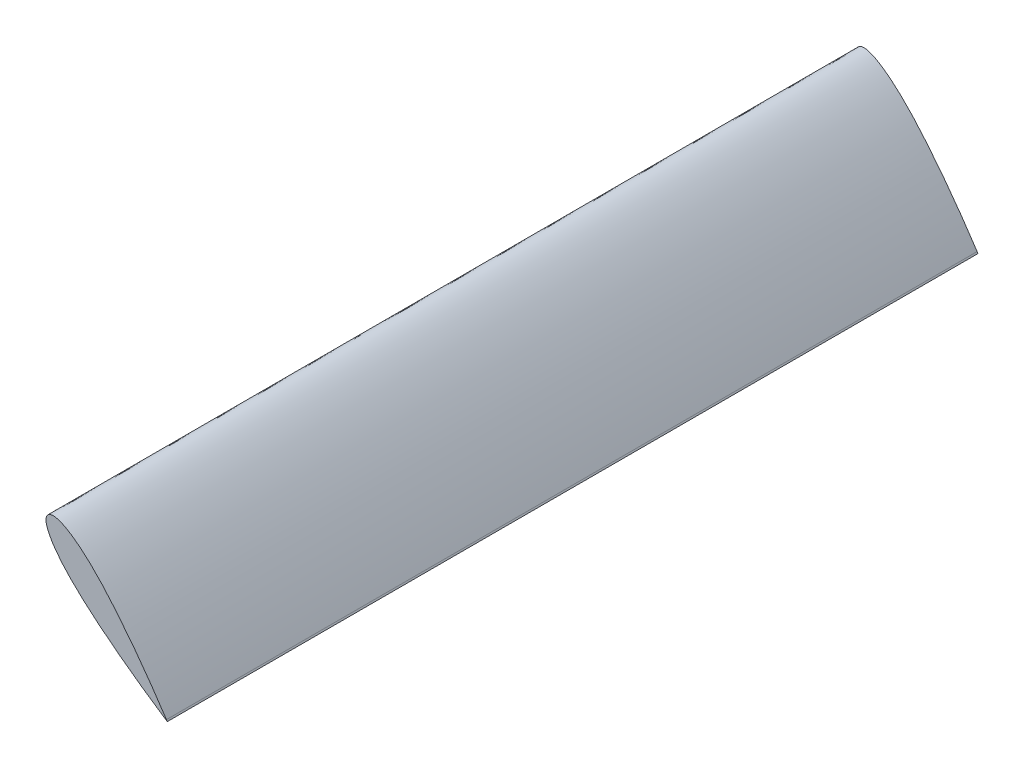
SolidWorks part; units mm, degrees
ref_plane "Front" through (0, 0, 0) normal (0, 0, 1) x (1, 0, 0)
ref_plane "Top" through (0, 0, 0) normal (0, 1, 0) x (1, 0, 0)
ref_plane "Right" through (0, 0, 0) normal (1, 0, 0) x (0, 0, -1)
curve "Curve1"
  spline degree 3 poles (1, 0.0019, 0) (0.9833, 0.0053, 0) (0.9501, 0.0122, 0) (0.8834, 0.025, 0) (0.8002, 0.0397, 0) (0.7001, 0.0553, 0) (0.6002, 0.0688, 0) (0.5002, 0.0799, 0) (0.4001, 0.0878, 0) (0.3167, 0.0906, 0) (0.25, 0.0895, 0) (0.1999, 0.0865, 0) (0.1497, 0.0808, 0) (0.1079, 0.0728, 0) (0.0746, 0.0633, 0) (0.0492, 0.0537, 0) (0.0279, 0.0421, 0) (0.0083, 0.0261, 0) (-0.0054, 0, 0) (0.0083, -0.0261, 0) (0.0279, -0.0421, 0) (0.0492, -0.0537, 0) (0.0746, -0.0633, 0) (0.1079, -0.0728, 0) (0.1497, -0.0808, 0) (0.1999, -0.0865, 0) (0.25, -0.0895, 0) (0.3167, -0.0906, 0) (0.4001, -0.0878, 0) (0.5002, -0.0799, 0) (0.6002, -0.0688, 0) (0.7001, -0.0553, 0) (0.8002, -0.0397, 0) (0.8834, -0.025, 0) (0.9501, -0.0122, 0) (0.9833, -0.0053, 0) (1, -0.0019, 0) knots 0 0 0 0 0.024604 0.049152 0.098109 0.146905 0.195555 0.244056 0.29241 0.340644 0.364754 0.388906 0.413178 0.437756 0.450305 0.46323 0.477068 0.485036 0.5 0.514964 0.522932 0.53677 0.549695 0.562244 0.586822 0.611094 0.635246 0.659356 0.70759 0.755944 0.804445 0.853095 0.901891 0.950848 0.975396 1 1 1 1
sketch "Sketch1" plane through (0, 0, 0) normal (0, 0, 1) x (1, 0, 0)
  line L0 (222.1989, 152.7695) -> (222.972, 152.2613)
  line L1 (222.4638, 153.0343) -> (222.972, 152.2613)
  line L2 (222.972, 152.2613) -> (152.2613, 222.972) construction
  line L5 (14.4712, -258.6476) -> (13.5477, -258.7012)
  line L6 (14.3743, -258.2858) -> (13.5477, -258.7012)
  line L7 (-238.0595, 127.3202) -> (-237.6441, 128.1468)
  line L8 (-237.6977, 127.2233) -> (-237.6441, 128.1468)
  circle A0 centre (0, 0) radius 31506.3021
  arc A2 (222.972, 152.2613) -> (152.2613, 222.972) centre (0, 0) ccw construction
  spline S1 degree 3 poles (222.4638, 153.0343) (221.5378, 154.4429) (219.688, 157.2569) (215.9143, 162.8194) (211.1075, 169.6832) (205.1944, 177.786) (199.1378, 185.7431) (192.9081, 193.5272) (186.4503, 201.0866) (180.7986, 207.1296) (176.0454, 211.7266) (172.3284, 215.028) (168.4114, 218.1426) (164.9246, 220.5081) (161.924, 222.1752) (159.468, 223.2839) (157.164, 223.9655) (154.6688, 224.2167) (151.8819, 223.3513) (151.0166, 220.5645) (151.2678, 218.0693) (151.9494, 215.7652) (153.058, 213.3093) (154.7251, 210.3086) (157.0906, 206.8218) (160.2052, 202.9049) (163.5066, 199.1879) (168.1036, 194.4347) (174.1467, 188.783) (181.7061, 182.3252) (189.4902, 176.0954) (197.4473, 170.0388) (205.55, 164.1257) (212.4139, 159.3189) (217.9764, 155.5453) (220.7904, 153.6954) (222.1989, 152.7695) knots 0 0 0 0 0.024604 0.049152 0.098109 0.146905 0.195555 0.244056 0.29241 0.340644 0.364754 0.388906 0.413178 0.437756 0.450305 0.46323 0.477068 0.485036 0.5 0.514964 0.522932 0.53677 0.549695 0.562244 0.586822 0.611094 0.635246 0.659356 0.70759 0.755944 0.804445 0.853095 0.901891 0.950848 0.975396 1 1 1 1
  point P3 (0, 0)
  point P5 (0, 0)
  point P8 (0, 0)
  point P9 (0, 0)
  dimension "D1" = 100
extrude "Boss-Extrude1" add sketch "Sketch1" along normal blind 480
ref_plane "Plane1" through (0, 0, 240) normal (0, 0, 1) x (1, 0, 0)
sketch "Sketch2" plane through (0, 0, 240) normal (0, 0, 1) x (1, 0, 0)
  line L0 (222.972, 152.2613) -> (152.2613, 222.972)
  line L1 (187.6166, 187.6166) -> (193.1503, 193.1503)
  line L2 (193.1503, 193.1503) -> (182.0829, 182.0829)
  spline S0 degree 3 poles (222.4638, 153.0343) (221.5378, 154.4429) (219.688, 157.2569) (215.9143, 162.8194) (211.1075, 169.6832) (205.1944, 177.786) (199.1378, 185.7431) (192.9081, 193.5272) (186.4503, 201.0866) (180.7986, 207.1296) (176.0454, 211.7266) (172.3284, 215.028) (168.4114, 218.1426) (164.9246, 220.5081) (161.924, 222.1752) (159.468, 223.2839) (157.164, 223.9655) (154.6688, 224.2167) (151.8819, 223.3513) (151.0166, 220.5645) (151.2678, 218.0693) (151.9494, 215.7652) (153.058, 213.3093) (154.7251, 210.3086) (157.0906, 206.8218) (160.2052, 202.9049) (163.5066, 199.1879) (168.1036, 194.4347) (174.1467, 188.783) (181.7061, 182.3252) (189.4902, 176.0954) (197.4473, 170.0388) (205.55, 164.1257) (212.4139, 159.3189) (217.9764, 155.5453) (220.7904, 153.6954) (222.1989, 152.7695) knots 0 0 0 0 0.024604 0.049152 0.098109 0.146905 0.195555 0.244056 0.29241 0.340644 0.364754 0.388906 0.413178 0.437756 0.450305 0.46323 0.477068 0.485036 0.5 0.514964 0.522932 0.53677 0.549695 0.562244 0.586822 0.611094 0.635246 0.659356 0.70759 0.755944 0.804445 0.853095 0.901891 0.950848 0.975396 1 1 1 1 construction
ref_plane "Plane2" through (187.6166, 187.6166, 0) normal (-0.7071, -0.7071, 0) x (0, 0, 1)
sketch "Sketch4" plane through (187.6166, 187.6166, 0) normal (-0.7071, -0.7071, 0) x (0, 0, 1)
  line L0 (480, 0.453) -> (405, 0.453) construction
  line L1 (480, -49.094) -> (480, 50) construction
  line L2 (405, 0.453) -> (382, 0.453) construction
  line L29 (384.6133, 3.4906) -> (382, 0.453) construction
  line L30 (389.1739, 8.7917) -> (391.7826, 11.824) construction
  line L31 (384.6133, 3.4906) -> (400.545, -0.9909) construction
  line L32 (395.9843, -6.292) -> (389.1739, 8.7917) construction
  line L33 (400.545, -0.9909) -> (389.1739, 8.7917) construction
  line L34 (384.6133, 3.4906) -> (389.1739, 8.7917) construction
  line L35 (395.9843, -6.292) -> (400.545, -0.9909) construction
  line L36 (395.9843, -6.292) -> (384.6133, 3.4906) construction
  line L37 (386.8913, 6.1385) -> (389.1739, 8.7917) construction
  line L38 (386.8913, 6.1385) -> (384.6087, 3.4853) construction
  line L39 (386.8913, 6.1385) -> (398.2623, -3.6441) construction
  line L40 (391.7826, 11.824) -> (405, 0.453) construction
  line L41 (395.2174, -10.9181) -> (405, 0.453) construction
  line L42 (382, 0.453) -> (391.7826, 11.824) construction
  line L43 (382, 0.453) -> (395.2174, -10.9181) construction
  line L44 (395.2174, -10.9181) -> (405, 0.453) construction
  line L45 (395.2174, 0.453) -> (395.2174, -10.9181) construction
  line L46 (405, 0.453) -> (395.2174, 0.453) construction
  line L47 (389.1739, 8.7917) -> (400.545, -0.9909)
  line L48 (391.7826, 11.824) -> (389.1739, 8.7917)
  line L49 (405, 0.453) -> (391.7826, 11.824)
  line L50 (395.2174, -10.9181) -> (405, 0.453)
  line L51 (382, 0.453) -> (395.2174, -10.9181)
  line L52 (384.6087, 3.4853) -> (382, 0.453)
  line L53 (395.9843, -6.292) -> (384.6087, 3.4853)
  line L54 (400.545, -0.9909) -> (395.9843, -6.292)
  point P68 (392.5791, 1.2499)
  dimension "D1" = 75
  dimension "D2" = 23
extrude "Boss-Extrude2" add sketch "Sketch4" along normal blind 30
pattern_linear "LPattern2" count 2 spacing 343 along (0, 0, -1) of "Boss-Extrude2"
